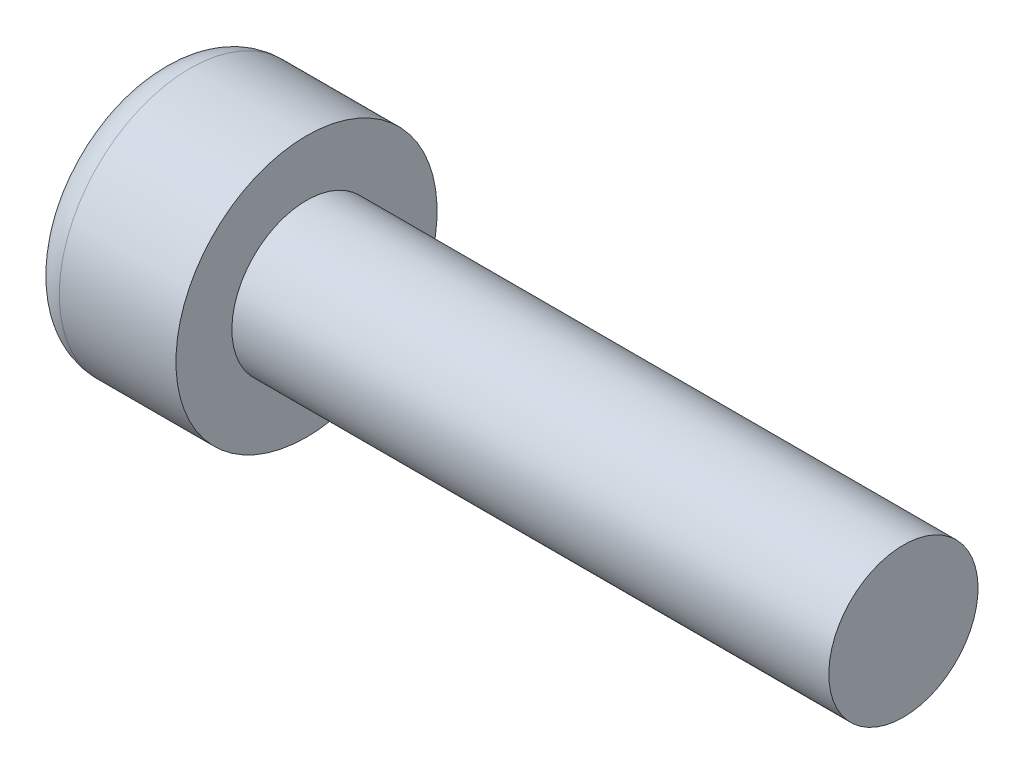
SolidWorks part; units mm, degrees
material "Plain Carbon Steel"
ref_plane "Front Plane" through (0, 0, 0) normal (0, 0, 1) x (1, 0, 0)
ref_plane "Top Plane" through (0, 0, 0) normal (0, 1, 0) x (1, 0, 0)
ref_plane "Right Plane" through (0, 0, 0) normal (1, 0, 0) x (0, 0, -1)
sketch "Sketch1" plane through (0, 0, 0) normal (0, 0, 1) x (1, 0, 0)
  line L0 (0, 0) -> (0, 2.625)
  line L1 (0.875, 3.5) -> (4, 3.5)
  line L2 (4, 3.5) -> (4, 2)
  line L3 (4, 2) -> (20, 2)
  line L4 (20, 2) -> (20, 0)
  line L5 (20, 0) -> (0, 0) construction
  line L6 (0.875, 2.625) -> (0.875, 1.75) construction
  line L7 (0.875, 1.75) -> (0.875, 0.875) construction
  line L8 (0.875, 0.875) -> (0.875, 0) construction
  line L9 (0.875, 3.5) -> (0.875, 2.625) construction
  line L10 (0, 0) -> (20, 0)
  arc A0 (0, 2.625) -> (0.875, 3.5) centre (0.875, 2.625) cw
  dimension "D1" = 4
  dimension "D2" = 7
  dimension "D3" = 4
  dimension "D4" = 16
revolve "Revolve1" add sketch "Sketch1" angle 360 about L10
sketch "Sketch2" plane through (0, 0, 0) normal (-1, 0, 0) x (0, 0, 1)
  line L1 (0, 1.7321) -> (-1.5, 0.866)
  line L2 (-1.5, 0.866) -> (-1.5, -0.866)
  line L3 (-1.5, -0.866) -> (0, -1.7321)
  line L4 (0, -1.7321) -> (1.5, -0.866)
  line L5 (1.5, -0.866) -> (1.5, 0.866)
  line L6 (1.5, 0.866) -> (0, 1.7321)
  circle A0 centre (0, 0) radius 1.5 construction
  dimension "D1" = 3
extrude "Cut-Extrude1" cut sketch "Sketch2" against normal blind 2
